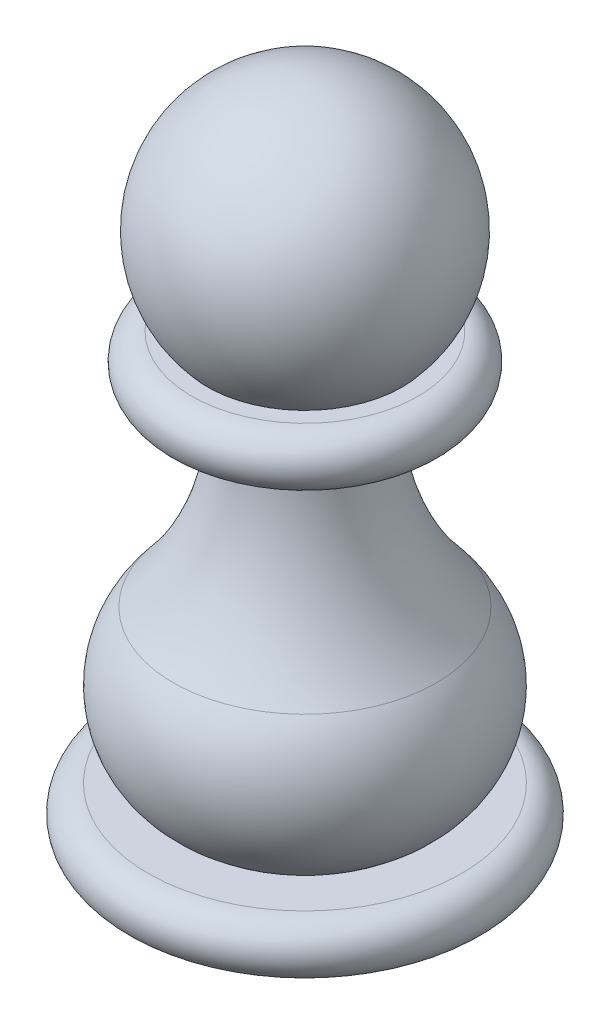
SolidWorks part; units mm, degrees
material "ABS"
ref_plane "Front Plane" through (0, 0, 0) normal (0, 0, 1) x (1, 0, 0)
ref_plane "Top Plane" through (0, 0, 0) normal (0, 1, 0) x (1, 0, 0)
ref_plane "Right Plane" through (0, 0, 0) normal (1, 0, 0) x (0, 0, -1)
sketch "Sketch1" plane through (0, 0, 0) normal (0, 0, 1) x (1, 0, 0)
  line L0 (0, 38) -> (0, 0) construction
  line L1 (5.5902, 25.5) -> (6.5, 25.5)
  line L2 (6.5, 22.5) -> (4, 22.5)
  line L3 (9, 3) -> (6.5, 3)
  line L4 (9, 0) -> (0, 0)
  line L5 (0, 7.8734) -> (3, 7.8734) construction
  line L6 (0, 38) -> (0, 0) construction
  line L7 (0, 38) -> (0, 0)
  line L8 (3, 7.8734) -> (9, 7.8734) construction
  arc A0 (5.5902, 25.5) -> (0, 38) centre (0, 30.5) ccw
  arc A1 (6.5, 25.5) -> (6.5, 22.5) centre (6.5, 24) cw
  arc A4 (9, 3) -> (9, 0) centre (9, 1.5) cw
  arc A6 (4, 22.5) -> (7.5621, 11.7704) centre (18.9675, 21.513) ccw
  arc A8 (6.5, 3) -> (7.5621, 11.7704) centre (3, 7.8734) ccw
  point P11 (7.0481, 6.8529)
  dimension "D2" = 7.5
  dimension "D3" = 1.5
  dimension "D5" = 15
  dimension "D7" = 9
  dimension "D8" = 38
  dimension "D11" = 1.5
  dimension "D12" = 6.5
  dimension "D9" = 6
  dimension "D1" = 12.5
  dimension "D4" = 6.5
  dimension "D6" = 4
  dimension "D10" = 9
revolve "Revolve4" add sketch "Sketch1" angle 360 about L7
